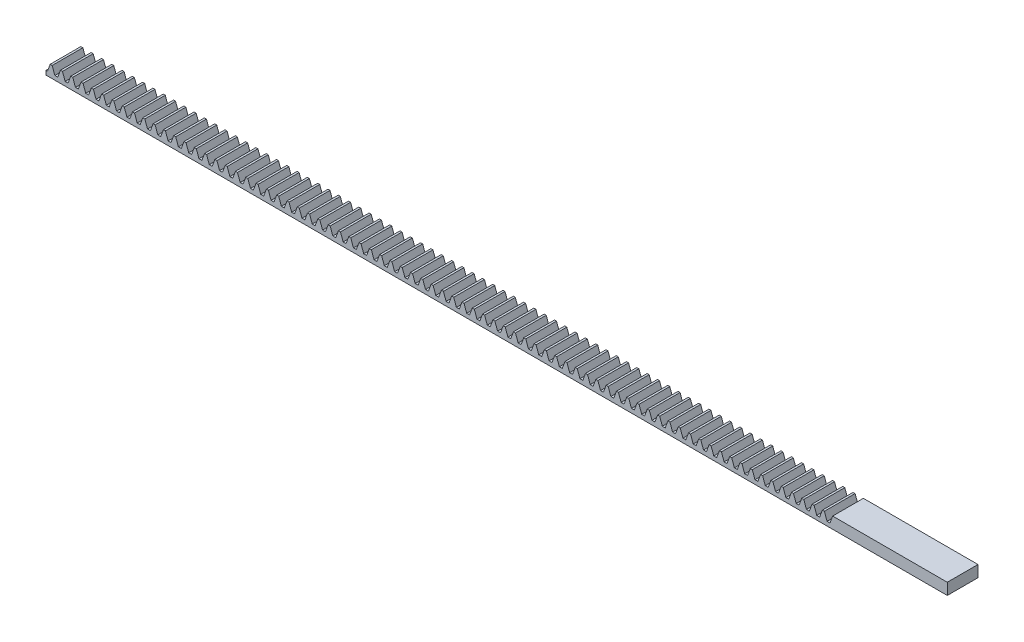
SolidWorks part; units mm, degrees
extrude "Blank" add sketch "BlankSke" against normal blind 7.5
sketch "BlankSke" plane through (0, 0, 0) normal (0, 0, 1) x (1, 0, 0)
  line L1 (0, 0) -> (220, 0)
  line L2 (0, 0) -> (0, 2.8)
  line L3 (0, 2.8) -> (220, 2.8)
  line L4 (220, 0) -> (220, 2.8)
  dimension "Length" = 220
  dimension "Blank_height" = 2.8
ref_plane "Plane1" through (0, 0, 0) normal (0, 0, 1) x (1, 0, 0)
ref_plane "Plane2" through (0, 0, 0) normal (0, 1, 0) x (1, 0, 0)
ref_plane "Plane3" through (0, 0, 0) normal (1, 0, 0) x (0, 0, -1)
other "Configuration Table"
sketch "HoldingSke" plane through (0, 0, 0) normal (0, 1, 0) x (1, 0, 0)
  line L0 (0, 0) -> (0.174, 1.2378)
  line L1 (-15, 0) -> (100, 0) construction
  line L2 (0, 0) -> (-2.1039, 2.3779)
  line L3 (0, 0) -> (-11.863, 4.5341)
  line L4 (0, 0) -> (1.9427, 8.4147)
  line L5 (0, 0) -> (-23.7986, -8.8762)
  line L6 (0, 0) -> (-10.5278, -7.1032)
  line L9 (-71.009, 38.7566) -> (107.5326, 103.7404)
  line L10 (-76.2, 3.1779) -> (-74.2, 3.1779)
  line L11 (0, 0) -> (-7.5, 0)
  line L12 (-76.2, 101.6) -> (-76.17, 101.6)
  line L13 (24.9733, 27.94) -> (52.9518, 28.4284)
  line L14 (24.9733, 27.94) -> (24.9743, 27.94)
  line L15 (24.9733, 27.94) -> (100.4006, 29.5858)
  circle A0 centre (0, 0) radius 19.05
  circle A1 centre (0, 0) radius 1
  circle A2 centre (0, 0) radius 12.7
  dimension "MPH" = 2
  dimension "Diameter" = 38.1
  dimension "Num_teeth" = 77
  dimension "Pitch" = 1.25
  dimension "Show_teeth" = 998
  dimension "Thickness" = 12.7
  dimension "Ap" = 20
  dimension "Pitch_height" = 2
  dimension "Width" = 7.5
  dimension "Backlash" = 0.03
  dimension "Addendum_fac" = 1
  dimension "Dedendum_fac" = 1.25
  dimension "Clearance_fac" = 0.25
  dimension "Dedendum_add" = 0.001
  dimension "Length" = 190
  dimension "Module" = 0.8
sketch "TooCutSkeIll" plane through (0, 0, 0) normal (0, 0, 1) x (1, 0, 0)
  line L0 (-1.0018, 2.7789) -> (-0.4025, 1.1323)
  line L1 (-0.2136, 1) -> (0.2136, 1)
  line L2 (0.4025, 1.1323) -> (1.0018, 2.7789)
  line L3 (220, 2.8) -> (0, 2.8) construction
  line L4 (0, 0) -> (0, 64.897) construction
  line L5 (-13.208, 2) -> (12.954, 2) construction
  line L6 (0, 0) -> (220, 0) construction
  line L7 (0.7183, 2) -> (0.7183, 48.7463) construction
  line L8 (-0.7183, 2) -> (-0.7183, 48.7463) construction
  line L9 (1.0319, 2.8) -> (1.0319, 2.8254)
  line L10 (-1.0319, 2.8) -> (-1.0319, 2.8254)
  line L11 (-1.0319, 2.8254) -> (1.0319, 2.8254)
  arc A0 (0.2136, 1) -> (0.4025, 1.1323) centre (0.2136, 1.201) ccw
  arc A1 (-0.4025, 1.1323) -> (-0.2136, 1) centre (-0.2136, 1.201) ccw
  arc A2 (1.0319, 2.8) -> (1.0018, 2.7789) centre (1.0319, 2.768) ccw
  arc A3 (-1.0018, 2.7789) -> (-1.0319, 2.8) centre (-1.0319, 2.768) ccw
  dimension "Pitch_height" = 2
  dimension "Addendum_plus" = 0.8254
  dimension "Pressure_angle" = 20
  dimension "Gap_width" = 1.4366
  dimension "Dedendum" = 1
extrude "ToothCutIll" [suppressed] cut sketch "TooCutSkeIll" against normal through all
sketch "TooCutSkeSim" plane through (0, 0, 0) normal (0, 0, 1) x (1, 0, 0)
  line L0 (0.3543, 1) -> (-0.3543, 1)
  line L1 (1.0187, 2.8254) -> (0.3543, 1)
  line L2 (0, 17.4625) -> (0, 53.467) construction
  line L3 (1.0187, 2.8254) -> (-1.0187, 2.8254)
  line L6 (-1.0187, 2.8254) -> (-0.3543, 1)
  line L9 (-0.7183, 2) -> (0.7183, 2) construction
  line L10 (0, 0) -> (220, 0) construction
  line L11 (0.7183, 2) -> (0.7183, 53.467) construction
  line L12 (-0.7183, 2) -> (-0.7183, 53.467) construction
  dimension "Pitch_height" = 2
  dimension "Addendum_plus" = 0.8254
  dimension "Pressure_angle" = 20
  dimension "Gap_width" = 1.4366
  dimension "Dedendum" = 1
extrude "ToothCutSim" cut sketch "TooCutSkeSim" against normal through all
pattern_linear "TeethCuts" count 77 spacing 2.5133 along (1, 0, 0) of "ToothCutIll", "ToothCutSim"
equation "' \"Module@HoldingSke\" = 6.35"
equation "' \"Num_teeth@HoldingSke\" = 12"
equation "' \"Ap@HoldingSke\" =  20"
equation "' \"Ap@HoldingSke\" = 20"
equation "' \"Width@HoldingSke\" = 0.25 * 25.4"
equation "' \"Show_teeth@HoldingSke\" = 500"
equation "' \"Backlash@HoldingSke\" = 0.009 * 25.4"
equation "' \"Addendum_fac@HoldingSke\" = 1.0"
equation "' \"Dedendum_fac@HoldingSke\" = 1.25"
equation "' \"Dedendum_add@HoldingSke\" = 0.00005 * 25.4"
equation "' \"Clearance_fac@HoldingSke\" = 0.25"
equation "' \"Pitch_height@HoldingSke\" = 1 * 25.4"
equation "' \"Length@HoldingSke\" = 4.71 * 25.4"
equation "\"Pitch@HoldingSke\" = 1 / \"Module@HoldingSke\""
equation "\"MPH@HoldingSke\" = \"Dedendum_fac@HoldingSke\" / \"Pitch@HoldingSke\" + 2 * \"Dedendum_add@HoldingSke\" + 0.002 * 25.4"
equation "\"MPH@HoldingSke\" = ((sgn( \"MPH@HoldingSke\" - \"Pitch_height@HoldingSke\")+1)*( \"MPH@HoldingSke\" - \"Pitch_height@HoldingSke\"))/2 + \"Pitch_height@HoldingSke\""
equation "\"Blank_height@BlankSke\" = \"Pitch_height@HoldingSke\" + \"Addendum_fac@HoldingSke\"  / \"Pitch@HoldingSke\" "
equation "\"Face_width@Blank\" = \"Width@HoldingSke\""
equation "\"Pressure_angle@TooCutSkeIll\" = \"Ap@HoldingSke\""
equation "\"Addendum_plus@TooCutSkeIll\" =  \"Addendum_fac@HoldingSke\"  / \"Pitch@HoldingSke\" + 0.001 *25.4"
equation "\"Dedendum@TooCutSkeIll\" = \"Dedendum_fac@HoldingSke\"  / \"Pitch@HoldingSke\""
equation "\"Pitch_height@TooCutSkeIll\" =  \"MPH@HoldingSke\""
equation "\"Gap_width@TooCutSkeIll\" = 3.14159265 / 2 / \"Pitch@HoldingSke\" + 6 * \"Backlash@HoldingSke\""
equation "\"Pressure_angle@TooCutSkeSim\" = \"Ap@HoldingSke\""
equation "\"Addendum_plus@TooCutSkeSim\" =  \"Addendum_fac@HoldingSke\"  / \"Pitch@HoldingSke\" + 0.001 * 25.4"
equation "\"Dedendum@TooCutSkeSim\" = \"Dedendum_fac@HoldingSke\"  / \"Pitch@HoldingSke\""
equation "\"Pitch_height@TooCutSkeSim\" =  \"MPH@HoldingSke\""
equation "\"Gap_width@TooCutSkeSim\" = 3.14159265 / 2 / \"Pitch@HoldingSke\" + 6 * \"Backlash@HoldingSke\""
equation "\"Root_fillet@TooCutSkeIll\" = \"Clearance_fac@HoldingSke\" / \"Pitch@HoldingSke\" + \"Dedendum_add@HoldingSke\""
equation "\"Break_rad@TooCutSkeIll\" = 0.02 / \"Pitch@HoldingSke\" * 2"
equation "\"Linear_pitch@TeethCuts\" = 3.14159265 / \"Pitch@HoldingSke\""
equation "\"Num_teeth@HoldingSke\" = int( ( \"Length@HoldingSke\" + 0 ) / (3.14159265 / \"Pitch@HoldingSke\")) + 0.9999  + 1"
equation " \"Num_teeth@TeethCuts\" = int( \"Show_teeth@HoldingSke\" ) + 1"
equation " \"Num_teeth@TeethCuts\" = ((sgn( \"Num_teeth@TeethCuts\" - \"Num_teeth@HoldingSke\" )-1)*( \"Num_teeth@TeethCuts\" - \"Num_teeth@HoldingSke\" ))/-2+ \"Num_teeth@HoldingSke\""
equation " \"Num_teeth@TeethCuts\" = ((sgn( \"Num_teeth@TeethCuts\" - 2.0)+1)*( \"Num_teeth@TeethCuts\" - 2.0))/2 +2.0"
